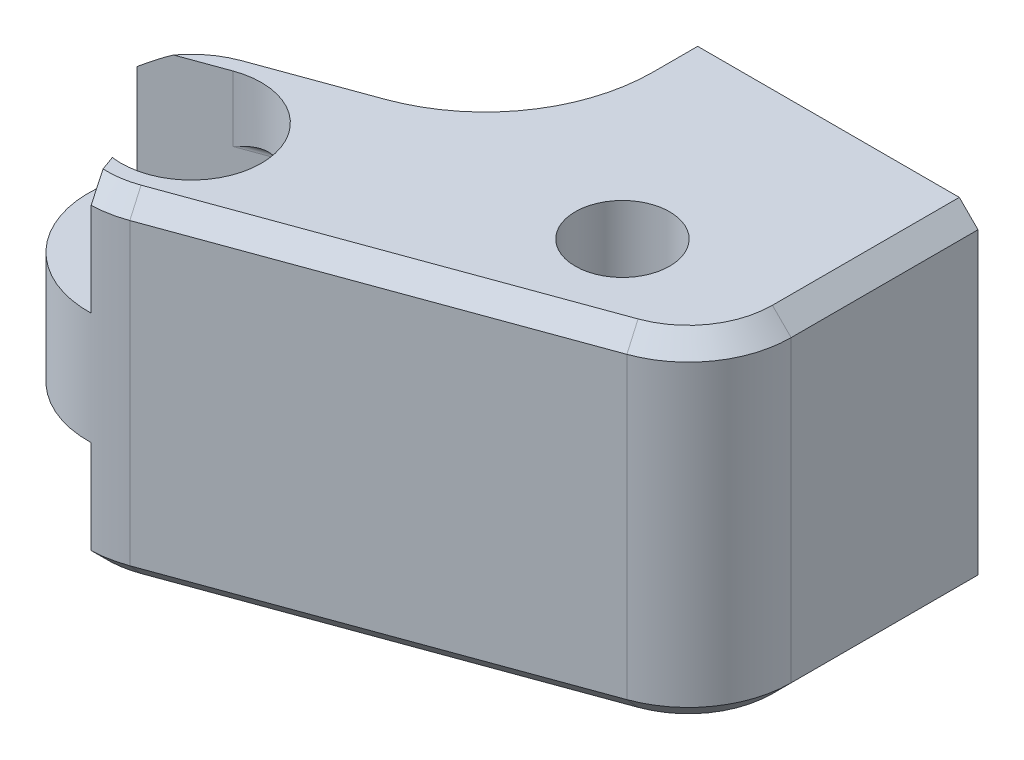
SolidWorks part; units mm, degrees
ref_plane "前视基准面" through (0, 0, 0) normal (0, 0, 1) x (1, 0, 0)
ref_plane "上视基准面" through (0, 0, 0) normal (0, 1, 0) x (1, 0, 0)
ref_plane "右视基准面" through (0, 0, 0) normal (1, 0, 0) x (0, 0, -1)
other "Configuration Table"
ref_plane "基准面1" through (0, 18, 0) normal (0, 1, 0) x (1, 0, 0)
sketch "草图1" plane through (0, 18, 0) normal (0, 1, 0) x (1, 0, 0)
  line L0 (-17.6189, -12.2657) -> (21.6618, 2.0313)
  line L1 (21.6618, 2.0313) -> (-10.5, 2.0313)
  line L2 (-10.5, 2.0313) -> (-21.3811, -1.9291)
  arc A0 (-21.3811, -1.9291) -> (-17.6189, -12.2657) centre (-19.5, -7.0974) ccw
  dimension "D1" = 5.5
  dimension "D2" = 32.1618
  dimension "D3" = 39.2807
  dimension "D4" = 41.1618
extrude "凸台-拉伸1" add sketch "草图1" against normal blind 15
sketch "草图2" plane through (0, 18, 0) normal (0, 1, 0) x (-1, 0, 0)
  line L0 (-21.6618, -2.0313) -> (-5.5, -2.0313)
  line L1 (-5.5, -2.0313) -> (-5.5, 3.8511)
  line L2 (-5.5, 3.8511) -> (-21.6618, -2.0313)
  dimension "D1" = 16.1618
  dimension "D2" = 1.922
  dimension "D3" = 3.9604
extrude "切除-拉伸1" cut sketch "草图2" against normal through all
sketch "草图3" plane through (0, 18, 0) normal (0, 1, 0) x (-1, 0, 0)
  line L0 (20.7826, 3.5736) -> (24.5633, 4.9496)
  line L1 (19.3611, 12.5957) -> (20.0101, 10.8126)
  line L2 (-5.5, -2.0313) -> (-5.5, 3.8511) construction
  line L3 (-5.5, -2.0313) -> (10.5, -2.0313) construction
  arc A0 (20.0101, 10.8126) -> (20.7826, 3.5736) centre (19.5, 7.0974) ccw
  arc A1 (24.5633, 4.9496) -> (19.3611, 12.5957) centre (19.5, 7.0974) ccw
  dimension "D1" = 3.75
  dimension "D2" = 5.5
  dimension "D3" = 24.8611
  dimension "D4" = 25
  dimension "D5" = 25.5101
  dimension "D6" = 26.2826
  dimension "D7" = 5.6049
extrude "切除-拉伸2" cut sketch "草图3" against normal blind 6
ref_plane "基准面2" through (0, 12, 0) normal (0, -1, 0) x (1, 0, 0)
sketch "草图4" plane through (0, 12, 0) normal (0, -1, 0) x (1, 0, 0)
  line L0 (-20.7826, 3.5736) -> (-18.0365, 2.5741)
  line L1 (-18.0365, 2.5741) -> (-17.5577, 3.8896)
  arc A0 (-17.5577, 3.8896) -> (-20.7826, 3.5736) centre (-19.5, 7.0974) cw
  dimension "D1" = 3.75
  dimension "D2" = 1.2826
  dimension "D3" = 2.7461
  dimension "D4" = 3.2249
extrude "切除-拉伸3" cut sketch "草图4" against normal blind 3
sketch "草图5" plane through (0, 3, 0) normal (0, -1, 0) x (1, 0, 0)
  line L0 (-17.2588, 2.291) -> (-16.78, 3.6066)
  line L1 (-16.78, 3.6066) -> (-17.5577, 3.8896)
  line L2 (-20.0101, 10.8126) -> (-19.3611, 12.5957)
  line L3 (-24.5633, 4.9496) -> (-17.2588, 2.291)
  line L4 (5.5, -2.0313) -> (5.5, 3.8511) construction
  arc A0 (-17.5577, 3.8896) -> (-20.0101, 10.8126) centre (-19.5, 7.0974) ccw
  arc A1 (-19.3611, 12.5957) -> (-24.5633, 4.9496) centre (-19.5, 7.0974) ccw
  dimension "D1" = 3.75
  dimension "D2" = 5.5
  dimension "D3" = 22.28
  dimension "D4" = 22.7588
  dimension "D5" = 23.0577
  dimension "D6" = 24.8611
  dimension "D7" = 25
  dimension "D8" = 25.5101
  dimension "D9" = 30.0633
  dimension "D10" = 0.3299
  dimension "D15" = 8.6591
  dimension "D16" = 9.9747
extrude "切除-拉伸4" cut sketch "草图5" against normal blind 3
sketch "草图6" plane through (-15.9762, 0, 5.8149) normal (-0.9397, 0, 0.342) x (0.342, 0, 0.9397)
  line L0 (-2.35, 3) -> (-2.35, 6)
  line L1 (-2.35, 6) -> (-3.75, 6)
  line L2 (-3.75, 6) -> (-3.75, 3)
  line L3 (-3.75, 3) -> (-2.35, 3)
  line L4 (-2.35, 6) -> (-2.35, 3) construction
  line L5 (-3.75, 3) -> (-2.35, 3) construction
  dimension "D1" = 1.4
  dimension "D2" = 3
extrude "切除-拉伸5" cut sketch "草图6" against normal blind 10.5001
sketch "草图7" plane through (-16.7539, 0, 6.0979) normal (-0.9397, 0, 0.342) x (0.342, 0, 0.9397)
  line L0 (-3.75, 12) -> (-2.35, 12)
  line L1 (-2.35, 12) -> (-2.35, 15)
  line L2 (-2.35, 15) -> (-3.75, 15)
  line L3 (-3.75, 15) -> (-3.75, 12)
  line L4 (-2.35, 15) -> (-2.35, 12) construction
  line L5 (-3.75, 12) -> (-2.35, 12) construction
  dimension "D1" = 1.4
  dimension "D2" = 3
extrude "切除-拉伸6" cut sketch "草图7" against normal blind 11.3277
sketch "草图8" plane through (0, 0, -2.0313) normal (0, 0, -1) x (-1, 0, 0)
  line L0 (-5.5, 3) -> (-5.5, 18)
  line L1 (-5.5, 18) -> (10.5, 18)
  line L2 (10.5, 18) -> (10.5, 3)
  line L3 (10.5, 3) -> (-5.5, 3)
  line L4 (-5.5, 3) -> (-5.5, 18) construction
  line L5 (-5.5, 3) -> (10.5, 3) construction
  dimension "D1" = 16
  dimension "D2" = 15
extrude "凸台-拉伸2" add sketch "草图8" along normal blind 7.9687
sketch "草图9" plane through (0, 3, 0) normal (0, -1, 0) x (1, 0, 0)
  line L0 (-17.6189, 12.2657) -> (5.5, 3.8511)
  line L1 (5.5, 3.8511) -> (5.5, -10)
  line L2 (5.5, -10) -> (-10.5, -10)
  line L3 (-10.5, -10) -> (-10.5, -2.0313)
  line L4 (-10.5, -2.0313) -> (-21.3811, 1.9291)
  line L5 (-24.5633, 4.9496) -> (-20.7826, 3.5736)
  line L6 (-20.0101, 10.8126) -> (-19.3611, 12.5957)
  line L7 (-10.5, -10) -> (-10.5, -2.0313) construction
  arc A0 (-19.3611, 12.5957) -> (-17.6189, 12.2657) centre (-19.5, 7.0974) cw
  arc A1 (-21.3811, 1.9291) -> (-24.5633, 4.9496) centre (-19.5, 7.0974) cw
  arc A2 (-20.7826, 3.5736) -> (-20.0101, 10.8126) centre (-19.5, 7.0974) ccw
  dimension "D1" = 5.5
  dimension "D2" = 5.5
  dimension "D3" = 3.75
  dimension "D4" = 16
  dimension "D5" = 7.1189
  dimension "D6" = 8.8611
  dimension "D7" = 9
  dimension "D8" = 9.5101
  dimension "D9" = 10.2826
  dimension "D10" = 10.8811
  dimension "D11" = 3.9604
  dimension "D12" = 11.9291
extrude "凸台-拉伸3" add sketch "草图9" along normal blind 3
hole_wizard "孔1" positions "草图11" profile "草图10" legacy
sketch "草图11" plane through (0, 0, -10) normal (0, 0, -1) x (-1, 0, 0)
  point P0 (4.5, 9)
sketch "草图10" plane through (-4.5, 9, -10) normal (1, 0, 0) x (0, 1, 0)
  line L0 (0, 0) -> (0, 7)
  line L1 (0, 7) -> (2.1, 7)
  line L2 (2.1, 7) -> (2.1, 0)
  line L3 (2.1, 0) -> (0, 0)
  line L4 (0, 110) -> (0, -10) construction
  dimension "直径" = 4.2
  dimension "深度" = 7
hole_wizard "孔2" positions "草图13" profile "草图12" legacy
sketch "草图13" plane through (0, 0, -10) normal (0, 0, -1) x (-1, 0, 0)
  point P0 (-0.5, 13)
sketch "草图12" plane through (0.5, 13, -10) normal (1, 0, 0) x (0, 1, 0)
  line L0 (0, 0) -> (0, 4)
  line L1 (0, 4) -> (1.015, 4)
  line L2 (1.015, 4) -> (1.015, 0)
  line L3 (1.015, 0) -> (0, 0)
  line L4 (0, 110) -> (0, -10) construction
  dimension "直径" = 2.03
  dimension "深度" = 4
hole_wizard "孔3" positions "草图15" profile "草图14" legacy
sketch "草图15" plane through (0, 0, -10) normal (0, 0, -1) x (-1, 0, 0)
  point P0 (-0.5, 5)
sketch "草图14" plane through (0.5, 5, -10) normal (1, 0, 0) x (0, 1, 0)
  line L0 (0, 0) -> (0, 4)
  line L1 (0, 4) -> (1.015, 4)
  line L2 (1.015, 4) -> (1.015, 0)
  line L3 (1.015, 0) -> (0, 0)
  line L4 (0, 110) -> (0, -10) construction
  dimension "直径" = 2.03
  dimension "深度" = 4
hole_wizard "孔4" positions "草图17" profile "草图16" legacy
sketch "草图17" plane through (0, 18, 0) normal (0, 1, 0) x (1, 0, 0)
  point P0 (-2.5855, -0.9411)
sketch "草图16" plane through (-2.5855, 18, 0.9411) normal (1, 0, 0) x (0, 0, 1)
  line L0 (0, 0) -> (0, 18)
  line L1 (0, 18) -> (2.525, 18)
  line L2 (2.525, 18) -> (2.525, 0)
  line L3 (2.525, 0) -> (0, 0)
  line L4 (0, 110) -> (0, -10) construction
  dimension "直径" = 5.05
  dimension "深度" = 18
hole_wizard "孔5" positions "草图19" profile "草图18" legacy
sketch "草图19" plane through (0, 12, 0) normal (0, 1, 0) x (1, 0, 0)
  point P0 (-19.5, -7.0974)
sketch "草图18" plane through (-19.5, 12, 7.0974) normal (1, 0, 0) x (0, 0, 1)
  line L0 (0, 0) -> (0, 12)
  line L1 (0, 12) -> (2.51, 12)
  line L2 (2.51, 12) -> (2.51, 0)
  line L3 (2.51, 0) -> (0, 0)
  line L4 (0, 110) -> (0, -10) construction
  dimension "直径" = 5.02
  dimension "深度" = 12
fillet "圆角1" radius 5.5 1 edges at (5.5, 9, 3.8511)
fillet "圆角2" radius 8 1 edges at (-10.5, 9, -2.0313)
chamfer "倒角1" distance 1 angle 45 16 edges at (-10.5, 0, -8.8165) (-23.2864, 0, 3.1083) (-11.9468, 0, -3.0443) (-18.5725, 0, 0.9069) (-18.4766, 0, 12.5014) (5.5, 0, -5) (-7.8689, 0, 8.717) (4.5053, 0, 3.1547) (-23.2864, 18, 3.1083) (-18.5725, 18, 0.9069) (-10.5, 18, -8.8165) (-11.9468, 18, -3.0443) (-18.4766, 18, 12.5014) (5.5, 18, -5) (-7.8689, 18, 8.717) (4.5053, 18, 3.1547)
fillet "圆角3" radius 0.5 7 edges at (-14.0873, 15, 1.1367) (-12.2354, 3, 1.9525) (-14.0873, 3, 1.1367) (-12.2354, 6, 1.9525) (-12.2354, 15, 1.9525) (-15.9776, 6, 1.8247) (-12.2354, 12, 1.9525)
